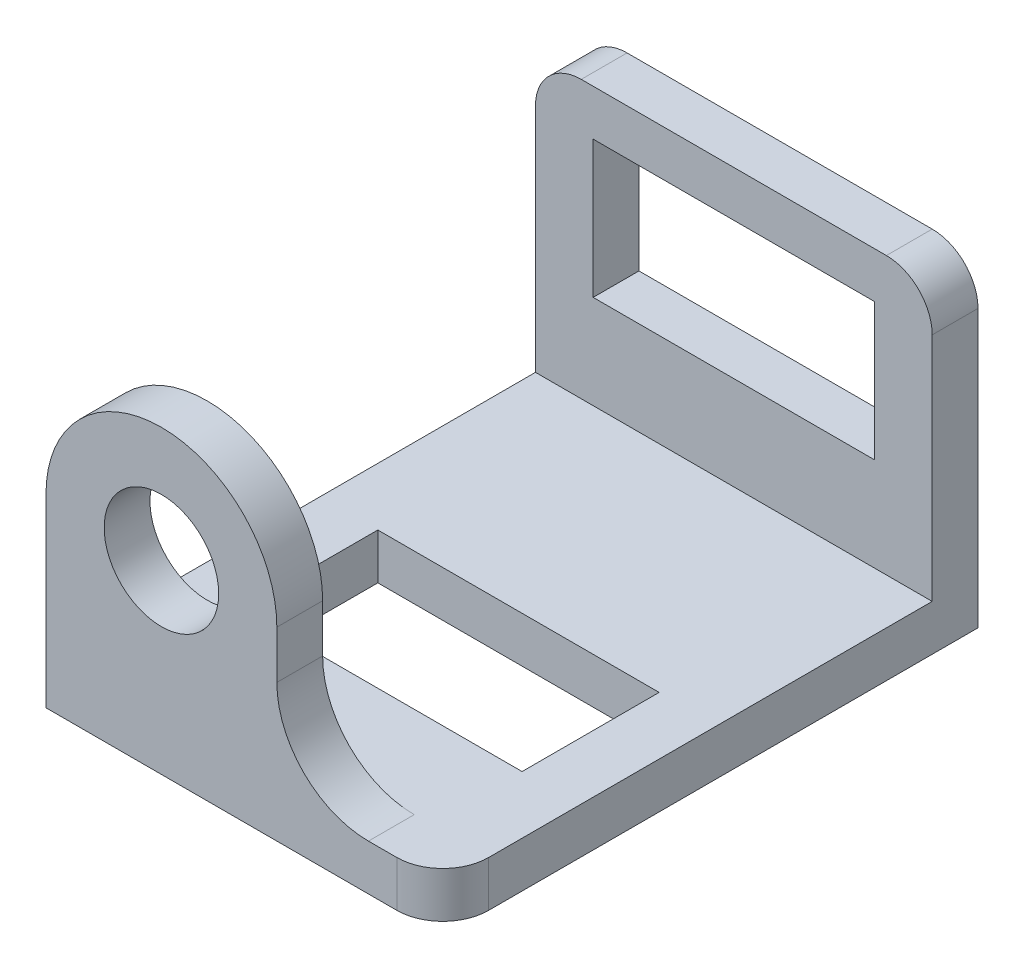
SolidWorks part; units mm, degrees
material "ABS PC"
ref_plane "Front Plane" through (0, 0, 0) normal (0, 0, 1) x (1, 0, 0)
ref_plane "Top Plane" through (0, 0, 0) normal (0, 1, 0) x (1, 0, 0)
ref_plane "Right Plane" through (0, 0, 0) normal (1, 0, 0) x (0, 0, -1)
sketch "Sketch1" plane through (0, 0, 0) normal (0, 1, 0) x (1, 0, 0)
  line L1 (-27.5, -28.5) -> (27.5, -28.5)
  line L2 (-27.5, -28.5) -> (-27.5, 45.702)
  line L3 (-27.5, 45.702) -> (27.5, 45.702)
  line L4 (27.5, -28.5) -> (27.5, 45.702)
  line L7 (-19.5, -9.5) -> (19.5, -9.5)
  line L8 (-19.5, -9.5) -> (-19.5, 9.5)
  line L9 (-19.5, 9.5) -> (19.5, 9.5)
  line L10 (19.5, -9.5) -> (19.5, 9.5)
  line L11 (-19.5, -9.5) -> (19.5, 9.5) construction
  line L12 (-19.5, 9.5) -> (19.5, -9.5) construction
  point P0 (0, 0)
  point P6 (0, 0)
  dimension "D1" = 36.202
  dimension "D2" = 55
  dimension "D3" = 19
  dimension "D4" = 39
  dimension "D5" = 8
  dimension "D6" = 8
  dimension "D7" = 19
extrude "Boss-Extrude1" add sketch "Sketch1" along normal blind 6.35
sketch "Sketch2" plane through (0, 0, -45.702) normal (0, 0, 1) x (1, 0, 0)
  line L14 (-19.5, 19.35) -> (19.5, 19.35)
  line L15 (-19.5, 38.35) -> (19.5, 38.35)
  line L21 (27.5, 6.35) -> (-27.5, 6.35) construction
  line L22 (-27.5, 6.35) -> (-27.5, 0) construction
  line L39 (-19.5, 38.35) -> (-19.5, 19.35)
  line L41 (27.5, 44.7) -> (-27.5, 44.7)
  line L42 (-27.5, 44.7) -> (-27.5, 6.35)
  line L43 (-27.5, 6.35) -> (27.5, 6.35)
  line L45 (19.5, 38.35) -> (19.5, 19.35)
  line L46 (27.5, 44.7) -> (27.5, 6.35)
  point P16 (0, 47.625)
  dimension "D1" = 19
  dimension "D2" = 39
  dimension "D4" = 13
  dimension "D7" = 8
  dimension "D8" = 55
  dimension "D5" = 6.35
  dimension "D6" = 8
extrude "Boss-Extrude2" add sketch "Sketch2" along normal blind 6.35 from surface at 0
sketch "Sketch12" plane through (0, 0, 28.5) normal (0, 0, 1) x (1, 0, 0)
  line L0 (-27.5, 25.68) -> (-27.5, 6.35)
  line L1 (19.5, 38.35) -> (-19.5, 38.35) construction
  line L2 (4.5, 25.68) -> (4.5, 6.35)
  line L3 (19.5, 19.35) -> (-19.5, 19.35) construction
  line L4 (-11.5, 16.35) -> (-11.5, 25.68) construction
  line L5 (-27.5, 6.35) -> (27.5, 6.35) construction
  line L6 (-27.5, 6.35) -> (4.5, 6.35)
  line L7 (-27.5, 0) -> (27.5, 0) construction
  line L8 (-27.5, 6.35) -> (-27.5, 0) construction
  arc A0 (4.5, 25.68) -> (-27.5, 25.68) centre (-11.5, 25.68) ccw
  circle A1 centre (-11.5, 25.68) radius 7.9375
  point P15 (0, 6.35)
  dimension "D4" = 15.875
  dimension "D2" = 19
  dimension "D1" = 25.68
  dimension "D5" = 16
extrude "Boss-Extrude11" add sketch "Sketch12" against normal blind 6.35
fillet "Fillet2" radius 12.7 1 edges at (4.5, 6.35, 25.325)
fillet "Fillet1" radius 6.35 3 edges at (27.5, 3.175, 28.5) (-27.5, 44.7, -42.527) (27.5, 44.7, -42.527)
